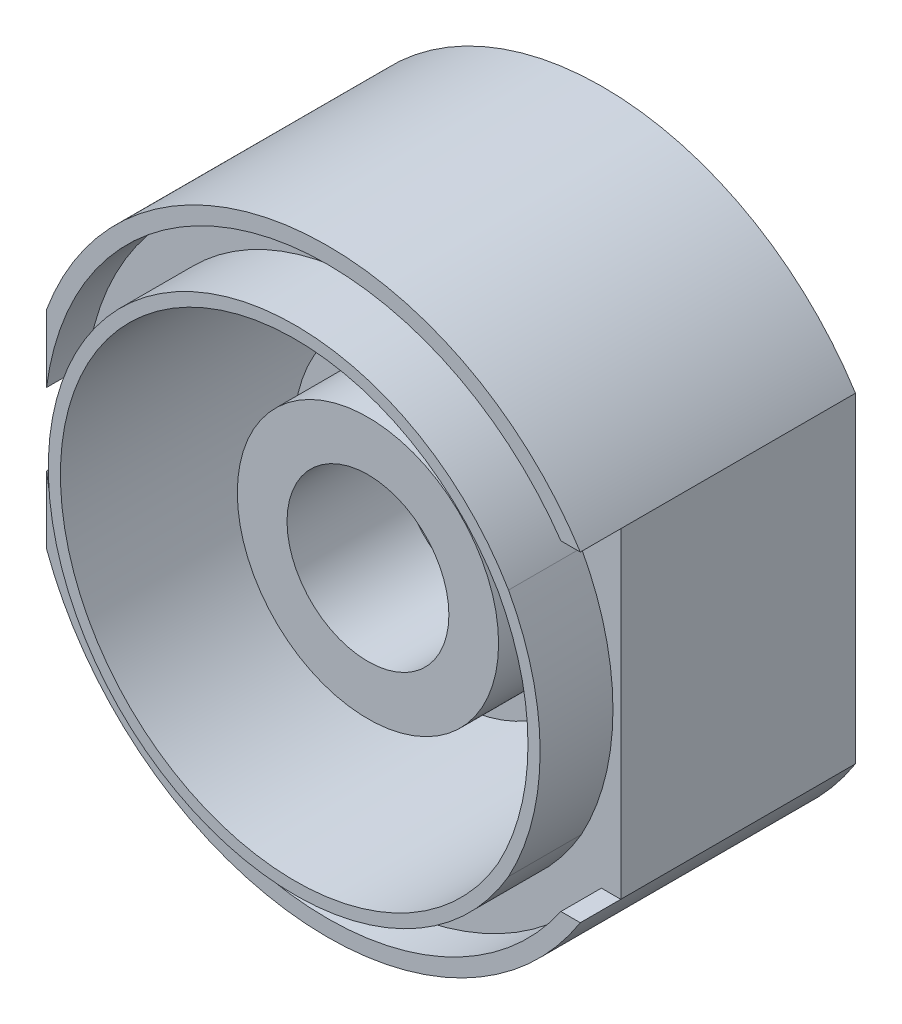
SolidWorks part; units mm, degrees
ref_plane "Front Plane" through (0, 0, 0) normal (0, 0, 1) x (1, 0, 0)
ref_plane "Top Plane" through (0, 0, 0) normal (0, 1, 0) x (1, 0, 0)
ref_plane "Right Plane" through (0, 0, 0) normal (1, 0, 0) x (0, 0, -1)
sketch "Sketch1" plane through (0, 0, 0) normal (0, 0, 1) x (1, 0, 0)
  line L0 (17.8759, 9.9153) -> (17.8759, -9.9153)
  arc A0 (17.8759, 9.9153) -> (17.8759, -9.9153) centre (2.2574, 0) ccw
extrude "Boss-Extrude1" add sketch "Sketch1" along normal blind 17
sketch "Sketch4" plane through (0, 0, 17) normal (0, 0, 1) x (1, 0, 0)
  line L2 (16.8759, -9.6203) -> (16.8759, 9.6203)
  line L3 (16.8759, -9.6203) -> (16.8759, 9.6203)
  arc A2 (16.8759, 9.6203) -> (16.8759, -9.6203) centre (2.2574, 0) ccw
  arc A3 (16.8759, 9.6203) -> (16.8759, -9.6203) centre (2.2574, 0) ccw
  dimension "D1" = 1
extrude "Cut-Extrude1" cut sketch "Sketch4" against normal blind 2.5
sketch "Sketch5" plane through (17.8759, 0, 0) normal (1, 0, 0) x (0, 0, -1)
  line L0 (-17, 9.9153) -> (-14.5, 9.9153)
  line L1 (-17, 9.9153) -> (0, 9.9153) construction
  line L2 (-14.5, 9.9153) -> (-14.5, -9.9153)
  line L3 (-17, -9.9153) -> (0, -9.9153) construction
  line L4 (-14.5, -9.9153) -> (-17, -9.9153)
  line L5 (-17, -9.9153) -> (-17, 9.9153)
extrude "Cut-Extrude2" cut sketch "Sketch5" against normal blind 2.5
sketch "Sketch6" plane through (0, 0, 14.5) normal (0, 0, 1) x (1, 0, 0)
  line L3 (15.6259, 7.6653) -> (15.4409, 7.6653)
  line L4 (15.4409, -7.6653) -> (15.6259, -7.6653)
  line L5 (15.6259, -7.6653) -> (15.6259, 7.6653)
  arc A1 (15.4409, 7.6653) -> (15.4409, -7.6653) centre (1.3758, 0) cw
  arc A2 (15.4409, 7.6653) -> (15.4409, -7.6653) centre (2.2574, 0) ccw
  arc A3 (15.4409, 7.6653) -> (15.4409, -7.6653) centre (2.2574, 0) ccw
  dimension "D1" = 2.25
extrude "Extrude-Thin1" add sketch "Sketch6" along normal blind 4.5 thin
sketch "Sketch8" plane through (0, 0, 0) normal (0, 0, -1) x (-1, 0, 0)
  line L0 (-2.2574, 18.5) -> (-2.2574, -18.5) construction
  arc A1 (-17.8759, -9.9153) -> (-17.8759, 9.9153) centre (-2.2574, 0) ccw construction
  circle A2 centre (-2.2574, 0) radius 8.5
  dimension "D1" = 17
extrude "Cut-Extrude4" cut sketch "Sketch8" against normal blind 6.5
sketch "Sketch9" plane through (0, 0, 6.5) normal (0, 0, -1) x (-1, 0, 0)
  circle A0 centre (-2.2574, 0) radius 5
  dimension "D1" = 10
extrude "Cut-Extrude5" cut sketch "Sketch9" against normal blind 27.5
sketch "Sketch10" plane through (0, 0, 6.5) normal (0, 0, -1) x (-1, 0, 0)
  circle A2 centre (-2.2574, 0) radius 6
  circle A3 centre (-2.2574, 0) radius 6
  dimension "D1" = 1
extrude "Cut-Extrude6" cut sketch "Sketch10" along normal blind 0.5 and the other way blind 1
sketch "Sketch14" plane through (0, 0, 14.5) normal (0, 0, 1) x (1, 0, 0)
  circle A2 centre (2.2574, 0) radius 9.5712
  arc A4 (14.7873, 7.2972) -> (14.7873, -7.2972) centre (2.2574, 0) ccw
  arc A11 (14.7873, 7.2972) -> (14.7873, -7.2972) centre (2.2574, 0) ccw
  arc A12 (14.7873, -7.2972) -> (14.7873, 7.2972) centre (1.3758, 0) ccw
  arc A13 (14.7873, -7.2972) -> (14.7873, 7.2972) centre (1.3758, 0) ccw
  point P3 (0, 0)
  point P4 (2.853, -0.308)
  dimension "D1" = 0
extrude "Cut-Extrude7" cut sketch "Sketch14" against normal blind 12.5
sketch "Sketch12" plane through (0, 0, 14.5) normal (0, 0, 1) x (1, 0, 0)
  circle A1 centre (2.2574, 0) radius 8.0712
  circle A2 centre (2.2574, 0) radius 8.0712
  dimension "D1" = 1.5
extrude "Cut-Extrude-Thin1" cut sketch "Sketch12" against normal blind 5 thin
sketch "Sketch15" plane through (0, 0, 0) normal (0, 0, 1) x (1, 0, 0)
  line L1 (-17.6886, 8.1082) -> (-15.1001, 8.1082)
  line L2 (-17.6886, 8.1082) -> (-17.6886, -9.0822)
  line L3 (-17.6886, -9.0822) -> (-15.1001, -9.0822)
  line L4 (-15.1001, 8.1082) -> (-15.1001, -9.0822)
  line L5 (-17.6886, 8.1082) -> (-15.1001, -9.0822) construction
  line L6 (-17.6886, -9.0822) -> (-15.1001, 8.1082) construction
  point P4 (-16.3943, -0.487)
extrude "Cut-Extrude8" cut sketch "Sketch15" along normal blind 31.5
